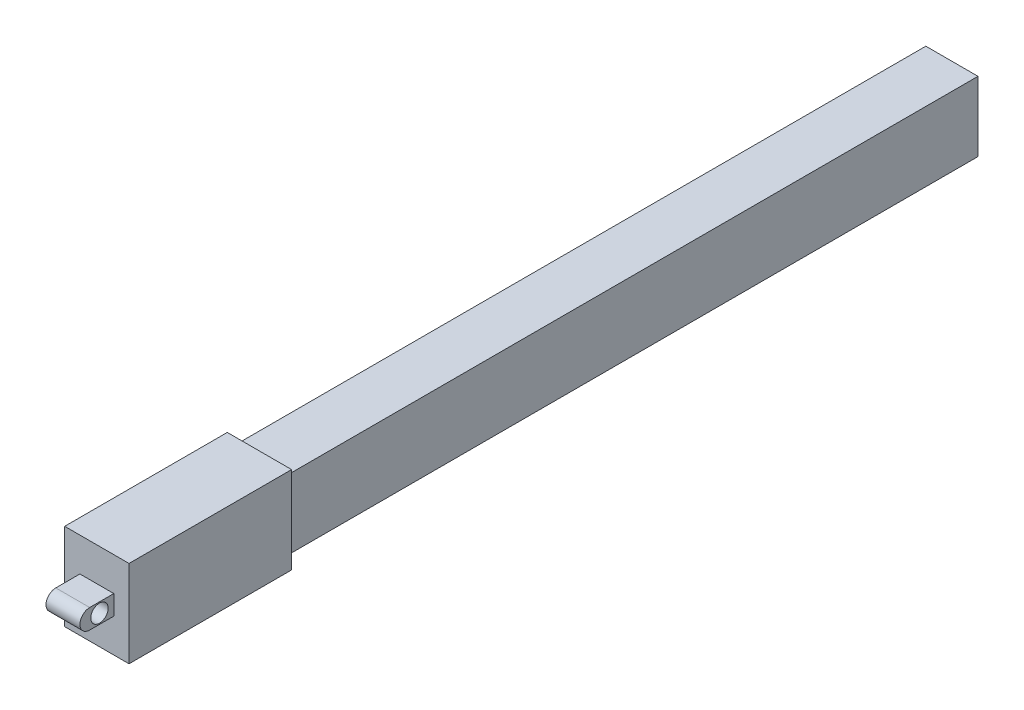
SolidWorks part; units mm, degrees
ref_plane "Front Plane" through (0, 0, 0) normal (0, 0, 1) x (1, 0, 0)
ref_plane "Top Plane" through (0, 0, 0) normal (0, 1, 0) x (1, 0, 0)
ref_plane "Right Plane" through (0, 0, 0) normal (1, 0, 0) x (0, 0, -1)
sketch "Sketch1" plane through (0, 0, 0) normal (0, 0, 1) x (1, 0, 0)
  line L1 (-6, -8) -> (6, -8)
  line L2 (-6, -8) -> (-6, 8)
  line L3 (-6, 8) -> (6, 8)
  line L4 (6, -8) -> (6, 8)
  line L5 (-6, -8) -> (6, 8) construction
  line L6 (-6, 8) -> (6, -8) construction
  point P0 (0, 0)
  dimension "D1" = 12
  dimension "D2" = 16
extrude "Boss-Extrude1" add sketch "Sketch1" along normal blind 159.3
sketch "Sketch2" plane through (0, 0, 159.3) normal (0, 0, 1) x (1, 0, 0)
  line L1 (-7.4, -10) -> (7.4, -10)
  line L2 (-7.4, -10) -> (-7.4, 10)
  line L3 (-7.4, 10) -> (7.4, 10)
  line L4 (7.4, -10) -> (7.4, 10)
  line L5 (-7.4, -10) -> (7.4, 10) construction
  line L6 (-7.4, 10) -> (7.4, -10) construction
  point P0 (0, 0)
  dimension "D1" = 14.8
  dimension "D2" = 20
extrude "Boss-Extrude2" add sketch "Sketch2" along normal blind 37.4
sketch "Sketch3" plane through (0, 0, 196.7) normal (0, 0, 1) x (1, 0, 0)
  line L1 (-3.9, -2.25) -> (3.9, -2.25)
  line L2 (-3.9, -2.25) -> (-3.9, 2.25)
  line L3 (-3.9, 2.25) -> (3.9, 2.25)
  line L4 (3.9, -2.25) -> (3.9, 2.25)
  line L5 (-3.9, -2.25) -> (3.9, 2.25) construction
  line L6 (-3.9, 2.25) -> (3.9, -2.25) construction
  point P0 (0, 0)
  dimension "D1" = 7.8
  dimension "D2" = 4.5
extrude "Boss-Extrude3" add sketch "Sketch3" along normal blind 7.8
sketch "Sketch4" plane through (-3.9, 0, 0) normal (-1, 0, 0) x (0, 0, 1)
  line L0 (204.5, 2.25) -> (204.5, -2.25) construction
  line L1 (204.5, -2.25) -> (196.7, -2.25) construction
  line L2 (204.5, 2.25) -> (196.7, 2.25) construction
  line L3 (204.5, -2.25) -> (202.25, -2.25)
  line L4 (204.5, 2.25) -> (204.5, -2.25)
  line L5 (204.5, 2.25) -> (202.25, 2.25)
  circle A0 centre (200, 0) radius 2
  arc A1 (202.25, -2.25) -> (202.25, 2.25) centre (202.25, 0) ccw
  line M2 (196.7, -2.25) -> (204.5, -2.25)
  line M3 (204.5, -2.25) -> (204.5, 2.25)
  line M4 (204.5, 2.25) -> (196.7, 2.25)
  dimension "D1" = 4
  dimension "D2" = 4.5
  dimension "D3" = 4.5
  dimension "D4" = 2.25
extrude "Cut-Extrude1" cut sketch "Sketch4" against normal through all contours A0 | A1 M2 M3 | A1 L4 M4
sketch "Sketch5" plane through (0, 0, 0) normal (0, 0, -1) x (-1, 0, 0)
  line L1 (-3.05, -4.5) -> (3.05, -4.5)
  line L2 (-3.05, -4.5) -> (-3.05, 4.5)
  line L3 (-3.05, 4.5) -> (3.05, 4.5)
  line L4 (3.05, -4.5) -> (3.05, 4.5)
  line L5 (-3.05, -4.5) -> (3.05, 4.5) construction
  line L6 (-3.05, 4.5) -> (3.05, -4.5) construction
  point P0 (0, 0)
  dimension "D1" = 6.1
  dimension "D2" = 9
extrude "Cut-Extrude2" cut sketch "Sketch5" against normal blind 192.2
sketch "Sketch7" plane through (0, 0, 0) normal (0, 0, -1) x (-1, 0, 0)
  circle A0 centre (0, 0) radius 5.4362
sketch "Sketch8" plane through (0, 0, 159.3) normal (0, 0, -1) x (-1, 0, 0)
  circle A0 centre (0, 0) radius 10
